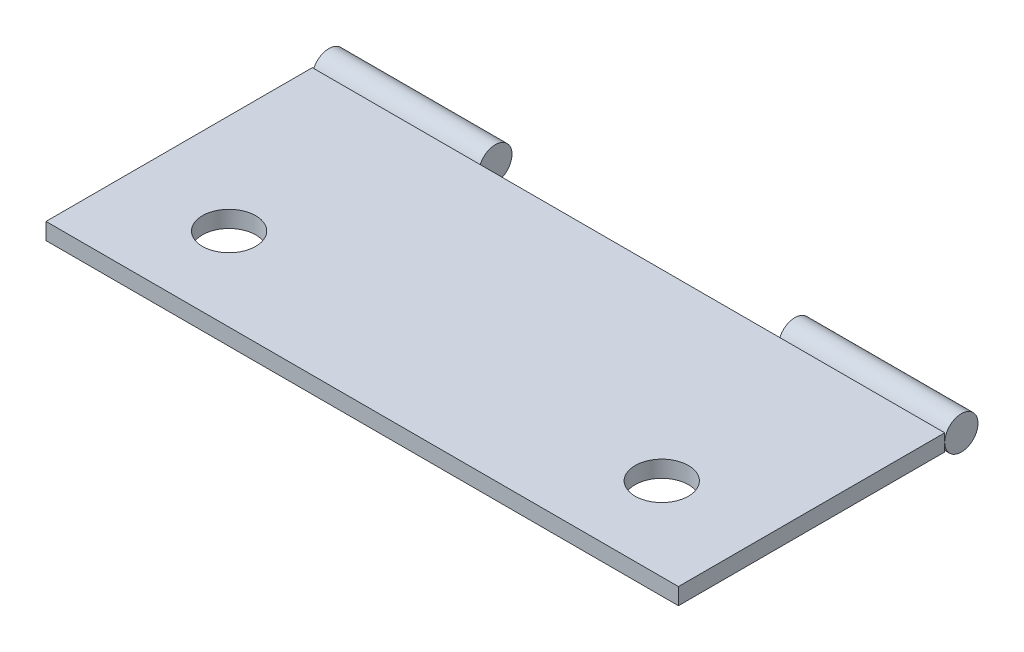
SolidWorks part; units mm, degrees
ref_plane "前视基准面" through (0, 0, 0) normal (0, 0, 1) x (1, 0, 0)
ref_plane "上视基准面" through (0, 0, 0) normal (0, 1, 0) x (1, 0, 0)
ref_plane "右视基准面" through (0, 0, 0) normal (1, 0, 0) x (0, 0, -1)
sketch "草图1" plane through (0, 0, 0) normal (0, 1, 0) x (1, 0, 0)
  line L1 (-19, 14.5) -> (19, 14.5)
  line L2 (-19, 14.5) -> (-19, -14.5)
  line L3 (-19, -14.5) -> (19, -14.5)
  line L4 (19, 14.5) -> (19, -14.5)
  line L5 (-19, 14.5) -> (19, -14.5) construction
  line L6 (-19, -14.5) -> (19, 14.5) construction
  point P0 (0, 0)
  dimension "D1" = 29
  dimension "D2" = 38
extrude "凸台-拉伸1" add sketch "草图1" along normal blind 1
sketch "草图2" plane through (0, 1, 0) normal (0, 1, 0) x (1, 0, 0)
  line L2 (-19, -14.5) -> (19, -14.5) construction
  line L3 (19, -14.5) -> (19, 14.5) construction
  line L5 (19, 14.5) -> (-19, 14.5) construction
  line L6 (0, 16.9538) -> (0, -18.9118) construction
  circle A0 centre (13, -9.5) radius 1.6
  circle A1 centre (13, 9.5) radius 1.3845
  circle A2 centre (-13, 9.5) radius 1.3845
  circle A3 centre (-13, -9.5) radius 1.6
  dimension "D1" = 5
  dimension "D2" = 6
  dimension "D3" = 5
  dimension "D4" = 6
extrude "切除-拉伸1" cut sketch "草图2" against normal up to next
sketch "草图3" plane through (0, 1, 0) normal (0, 1, 0) x (1, 0, 0)
  line L0 (-19, 1.5) -> (19, 1.5)
  line L1 (-19, 14.5) -> (-19, -14.5) construction
  line L2 (19, -14.5) -> (19, 14.5) construction
  line L3 (-19, -14.5) -> (19, -14.5) construction
  line L4 (-19, 1.5) -> (-19, 14.5)
  line L5 (-19, 14.5) -> (19, 14.5)
  line L6 (19, 14.5) -> (19, 1.5)
  dimension "D1" = 16
extrude "切除-拉伸2" cut sketch "草图3" against normal blind 8
sketch "草图5" plane through (19, 0, 0) normal (1, 0, 0) x (0, 0, -1)
  line L0 (1.5, 0) -> (1.5, 1) construction
  circle A0 centre (2.5, 0.4969) radius 1
  point P2 (2.5971, 0.4969)
  dimension "D1" = 2
extrude "凸台-拉伸2" add sketch "草图5" against normal up to surface (38 mm away) separate body up to face at (-19, 0.5, 6.5)
sketch "草图6" plane through (0, 1, 0) normal (0, 1, 0) x (1, 0, 0)
  line L0 (0, 0) -> (0, 8.305) construction
  line L1 (-19, 1.5) -> (19, 1.5) construction
  line L2 (-9, 1.5) -> (9, 1.5)
  line L3 (-9, 1.5) -> (-9, 5.3588)
  line L4 (-9, 5.3588) -> (9, 5.3588)
  line L5 (9, 1.5) -> (9, 5.3588)
  point P7 (7.9733, -3.4272)
  point P10 (0, 0)
  point P11 (0, 8.305)
  point P12 (0, 1.5)
  dimension "D1" = 18
extrude "切除-拉伸3" cut sketch "草图6" against normal through all both and the other way through all
